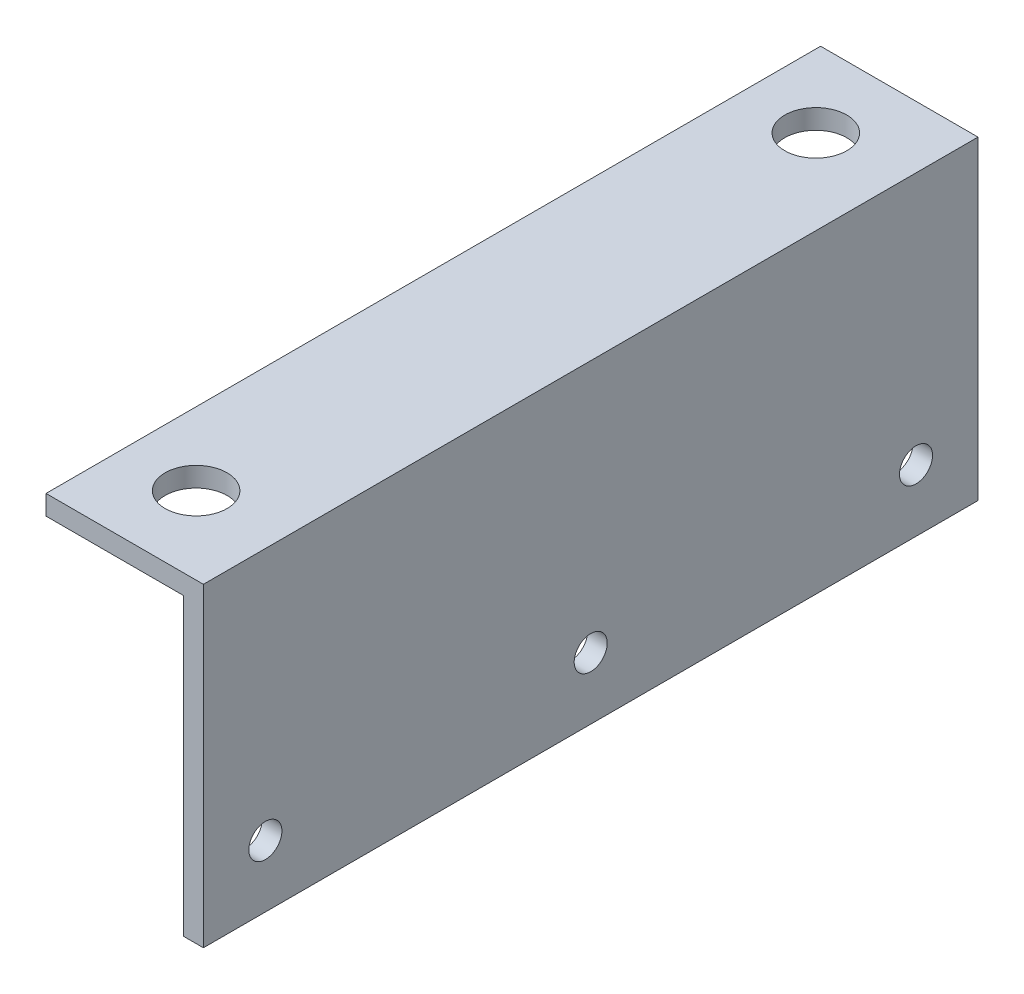
SolidWorks part; units mm, degrees
ref_plane "Front Plane" through (0, 0, 0) normal (0, 0, 1) x (1, 0, 0)
ref_plane "Top Plane" through (0, 0, 0) normal (0, 1, 0) x (1, 0, 0)
ref_plane "Right Plane" through (0, 0, 0) normal (1, 0, 0) x (0, 0, -1)
sketch "Sketch1" plane through (0, 0, 0) normal (0, 0, 1) x (1, 0, 0)
  line L0 (0, 0) -> (0, 50.8)
  line L1 (0, 50.8) -> (-25.4, 50.8)
  line L2 (-3.175, 0) -> (-3.175, 47.625)
  line L3 (-3.175, 47.625) -> (-25.4, 47.625)
  line L4 (-25.4, 50.8) -> (-25.4, 47.625)
  line L5 (-3.175, 0) -> (0, 0)
  dimension "D1" = 25.4
  dimension "D2" = 50.8
  dimension "D3" = 3.175
extrude "Boss-Extrude1" add sketch "Sketch1" along normal blind 125
sketch "Sketch2" plane through (0, 0, 0) normal (1, 0, 0) x (0, 0, -1)
  line L0 (-125, 10) -> (0, 10) construction
  line L1 (-125, 0) -> (-125, 50.8) construction
  line L2 (0, 0) -> (0, 50.8) construction
  line L3 (-125, 0) -> (0, 0) construction
  circle A0 centre (-115, 10) radius 2.665
  circle A1 centre (-10, 10) radius 2.665
  circle A2 centre (-62.5, 10) radius 2.665
  dimension "D2" = 5.33
  dimension "D3" = 10
  dimension "D4" = 10
  dimension "D1" = 10
extrude "Cut-Extrude1" cut sketch "Sketch2" against normal up to next
sketch "Sketch3" plane through (0, 50.8, 0) normal (0, 1, 0) x (1, 0, 0)
  line L0 (0, -62.5) -> (-25.4, -62.5) construction
  line L1 (0, -125) -> (0, 0) construction
  line L2 (-25.4, -125) -> (-25.4, 0) construction
  arc A0 (-13.675, -7.5) -> (-13.675, -17.5) centre (-13.675, -12.5) ccw construction
  arc A1 (-13.675, -7.5) -> (-13.675, -17.5) centre (-13.675, -12.5) ccw
  circle A2 centre (-13.675, -12.5) radius 5
  circle A3 centre (-13.675, -112.5) radius 5
extrude "Cut-Extrude2" cut sketch "Sketch3" against normal up to next contours A3 | A1 A2
